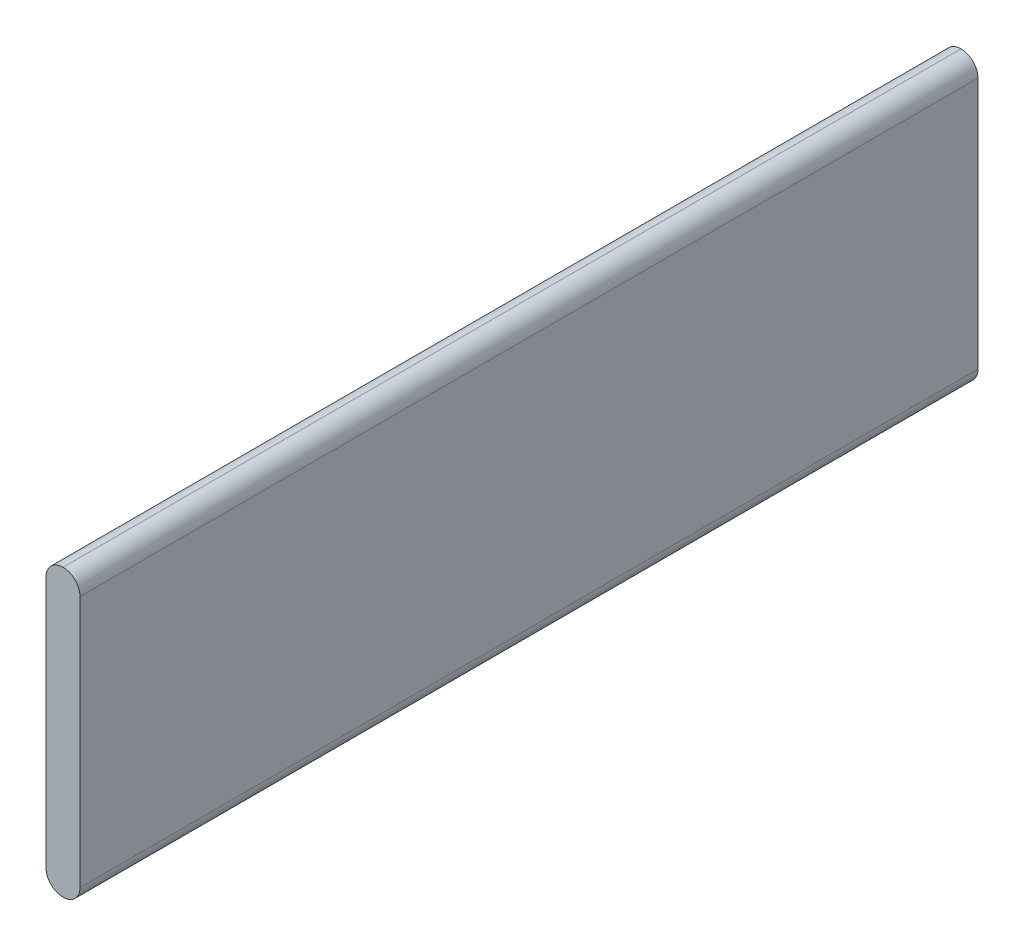
SolidWorks part; units mm, degrees
ref_plane "Plan de face" through (0, 0, 0) normal (0, 0, 1) x (1, 0, 0)
ref_plane "Plan de dessus" through (0, 0, 0) normal (0, 1, 0) x (1, 0, 0)
ref_plane "Plan de droite" through (0, 0, 0) normal (1, 0, 0) x (0, 0, -1)
sketch "Esquisse1" plane through (0, 0, 0) normal (0, 0, 1) x (1, 0, 0)
  line L1 (-9.9817, 18.917) -> (-9.9617, 18.917)
  line L2 (-11.2217, 17.677) -> (-11.2217, -0.843)
  line L3 (-9.9817, -2.083) -> (-9.9617, -2.083)
  line L4 (-8.7217, 17.677) -> (-8.7217, -0.843)
  arc A0 (-9.9617, 18.917) -> (-8.7217, 17.677) centre (-9.9617, 17.677) cw
  arc A1 (-11.2217, 17.677) -> (-9.9817, 18.917) centre (-9.9817, 17.677) cw
  arc A2 (-11.2217, -0.843) -> (-9.9817, -2.083) centre (-9.9817, -0.843) ccw
  arc A3 (-8.7217, -0.843) -> (-9.9617, -2.083) centre (-9.9617, -0.843) cw
  point P12 (-8.7217, -2.083)
  dimension "D3" = 1.24
  dimension "D4" = 1.24
  dimension "D1" = 2.5
  dimension "D2" = 21
extrude "Extrusion1" add sketch "Esquisse1" along normal blind 66
